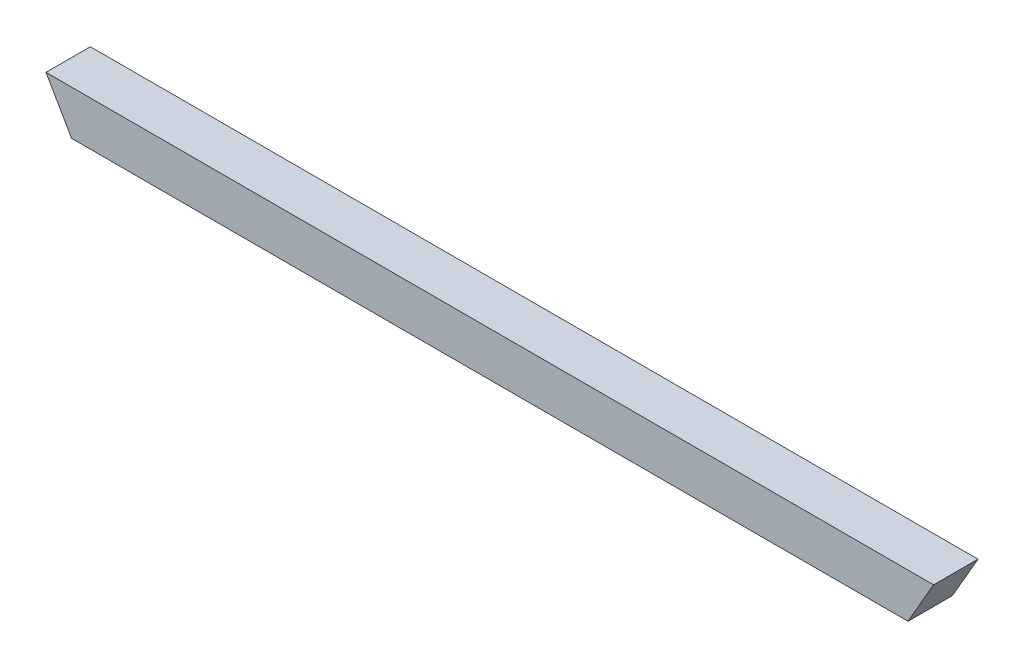
SolidWorks part; units mm, degrees
ref_plane "Front Plane" through (0, 0, 0) normal (0, 0, 1) x (1, 0, 0)
ref_plane "Top Plane" through (0, 0, 0) normal (0, 1, 0) x (1, 0, 0)
ref_plane "Right Plane" through (0, 0, 0) normal (1, 0, 0) x (0, 0, -1)
sketch "Sketch2" plane through (0, 0, 0) normal (0, 0, 1) x (1, 0, 0)
  line L0 (-200, 0) -> (200, 0)
  line L1 (0, 0) -> (0, -20) construction
  line L2 (-200, 0) -> (-183.0943, -29.2815) construction
  line L3 (188.453, -20) -> (-188.453, -20)
  line L4 (200, 0) -> (188.453, -20)
  line L5 (-200, 0) -> (-188.453, -20)
  point P4 (0, 0)
  point P10 (0, -20)
  dimension "D1" = 60
  dimension "D2" = 400
extrude "Boss-Extrude1" add sketch "Sketch2" along normal blind 20
